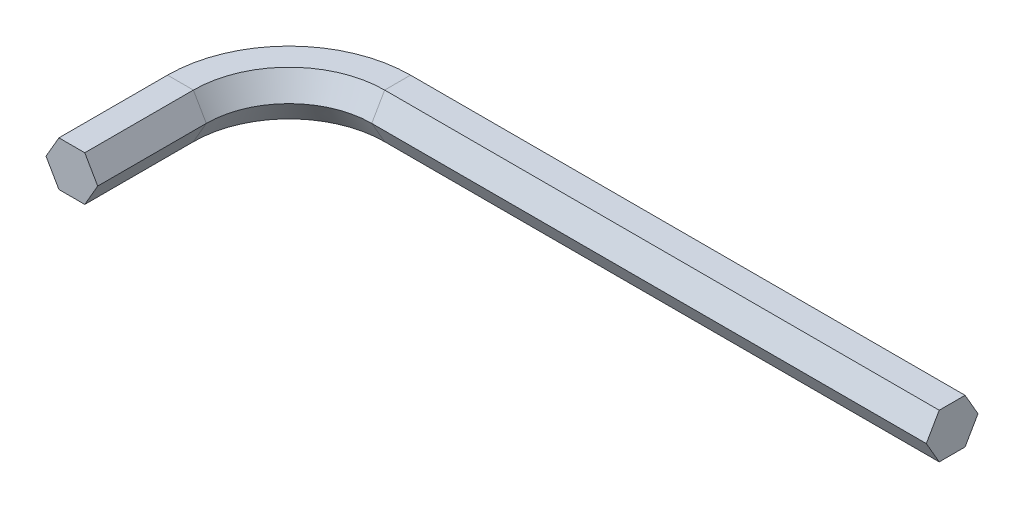
SolidWorks part; units mm, degrees
ref_plane "Front Plane" through (0, 0, 0) normal (0, 0, 1) x (1, 0, 0)
ref_plane "Top Plane" through (0, 0, 0) normal (0, 1, 0) x (1, 0, 0)
ref_plane "Right Plane" through (0, 0, 0) normal (1, 0, 0) x (0, 0, -1)
sketch "Sketch2" plane through (0, 0, 0) normal (0, 1, 0) x (1, 0, 0)
  line L0 (0, 0) -> (0, 28)
  line L1 (28, 56) -> (171, 56)
  arc A0 (0, 28) -> (28, 56) centre (28, 28) cw
  dimension "D1" = 28
  dimension "D2" = 56
  dimension "D3" = 171
sketch "Sketch3" plane through (0, 0, 0) normal (0, 0, 1) x (1, 0, 0)
  line L1 (3.3333, 5.7735) -> (-3.3333, 5.7735)
  line L2 (-3.3333, 5.7735) -> (-6.6667, 0)
  line L3 (-6.6667, 0) -> (-3.3333, -5.7735)
  line L4 (-3.3333, -5.7735) -> (3.3333, -5.7735)
  line L5 (3.3333, -5.7735) -> (6.6667, 0)
  line L6 (6.6667, 0) -> (3.3333, 5.7735)
  circle A0 centre (0, 0) radius 5.7735 construction
  point P1 (5, 2.8868)
  point P10 (0, 0)
  point P11 (0, 5.7735)
  dimension "5" = 5
sweep "Sweep1" add profiles "Sketch3" path "Sketch2"
